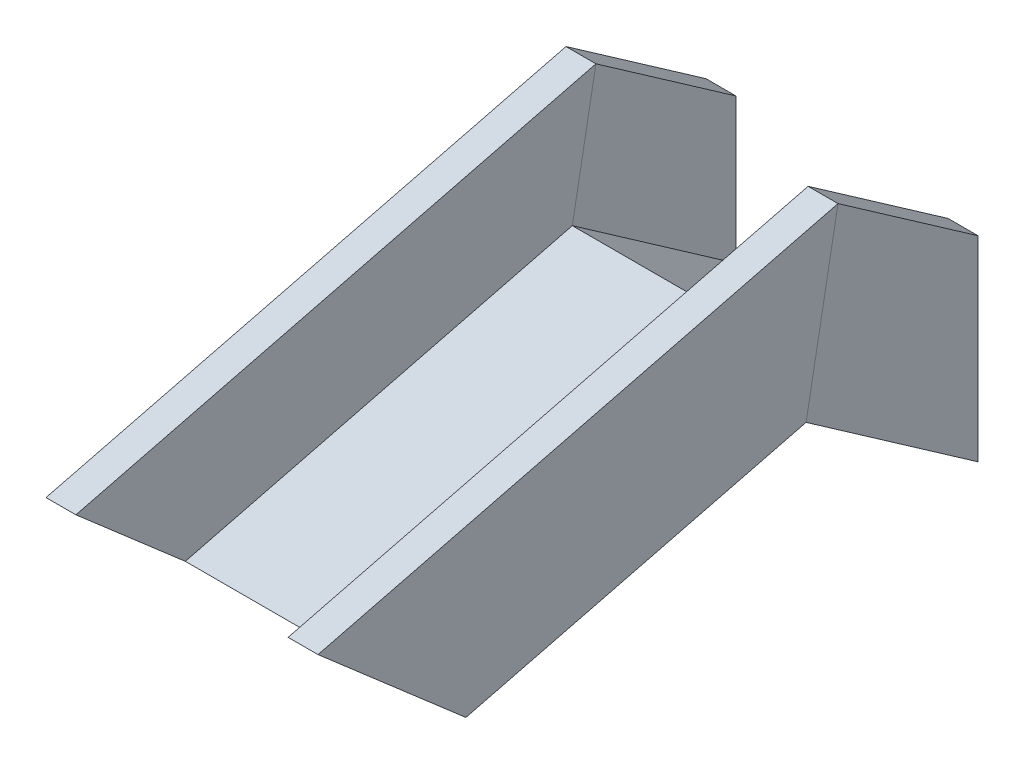
SolidWorks part; units mm, degrees
ref_plane "Front Plane" through (0, 0, 0) normal (0, 0, 1) x (1, 0, 0)
ref_plane "Top Plane" through (0, 0, 0) normal (0, 1, 0) x (1, 0, 0)
ref_plane "Right Plane" through (0, 0, 0) normal (1, 0, 0) x (0, 0, -1)
sketch "Sketch1" plane through (0, 0, 0) normal (0, 0, 1) x (1, 0, 0)
  line L0 (0, 0) -> (0, 36.5742)
  line L1 (0, 36.5742) -> (5.5865, 36.5742)
  line L2 (5.5865, 36.5742) -> (5.5865, 9.5145)
  line L3 (5.5865, 9.5145) -> (45.2159, 9.5145)
  line L4 (45.2159, 9.5145) -> (45.2159, 36.5742)
  line L5 (45.2159, 36.5742) -> (50.8024, 36.5742)
  line L6 (50.8024, 36.5742) -> (50.8024, 0)
  line L7 (50.8024, 0) -> (0, 0)
sketch "Sketch2" plane through (0, 0, 0) normal (1, 0, 0) x (0, 0, -1)
  line L0 (0, 0) -> (-32.1045, 22.4315)
  line L1 (-32.1045, 22.4315) -> (-95.6457, 6.4742)
  point P3 (-20.2882, 16.7264)
  point P5 (-95.6457, 6.4742)
  point P6 (-32.1045, 22.4315)
sweep "Sweep1" add profiles "Sketch1" path "Sketch2"
